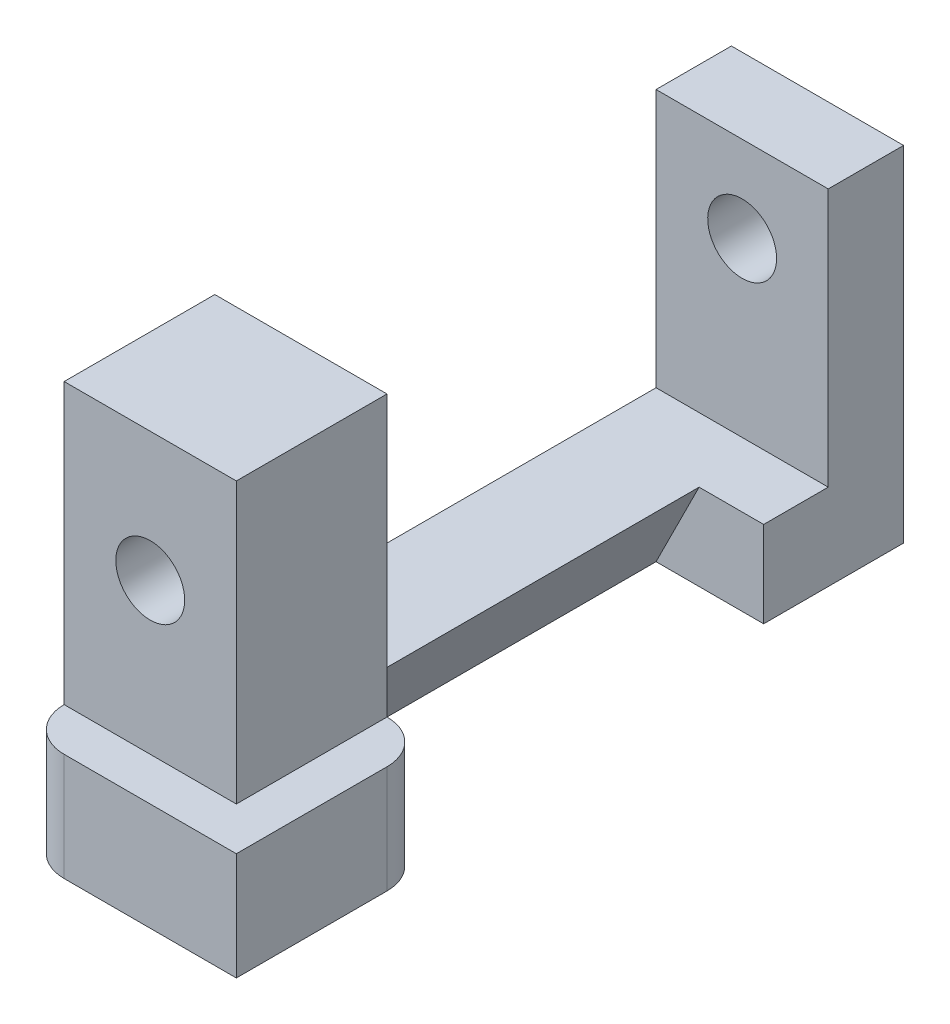
SolidWorks part; units mm, degrees
ref_plane "Front Plane" through (0, 0, 0) normal (0, 0, 1) x (1, 0, 0)
ref_plane "Top Plane" through (0, 0, 0) normal (0, 1, 0) x (1, 0, 0)
ref_plane "Right Plane" through (0, 0, 0) normal (1, 0, 0) x (0, 0, -1)
sketch "Sketch1" plane through (0, 0, 0) normal (1, 0, 0) x (0, 0, -1)
  line L0 (0, 0) -> (0, 16)
  line L1 (0, 16) -> (-3.5, 16)
  line L2 (-3.5, 16) -> (-3.5, 4)
  line L3 (-3.5, 4) -> (-24, 4)
  line L4 (-24, 4) -> (-24, 18)
  line L5 (-24, 18) -> (-31, 18)
  line L6 (-31, 18) -> (-31, 0)
  line L7 (-31, 0) -> (0, 0)
  dimension "D1" = 3.5
  dimension "D2" = 16
  dimension "D3" = 12
  dimension "D4" = 18
  dimension "D5" = 31
  dimension "D6" = 7
extrude "Boss-Extrude1" add sketch "Sketch1" against normal blind 8
sketch "Sketch3" plane through (-8, 0, 0) normal (-1, 0, 0) x (0, 0, 1)
  line L0 (3.5, 16) -> (3.5, 4) construction
  line L1 (3.5, 4) -> (24, 4)
  line L2 (3.5, 4) -> (3.5, 0)
  line L3 (3.5, 0) -> (24, 0)
  line L4 (24, 4) -> (24, 0)
  line L5 (24, 4) -> (24, 18) construction
  line L6 (31, 0) -> (0, 0) construction
  line L7 (3.5, 4) -> (24, 4) construction
extrude "Cut-Extrude1" [suppressed] cut sketch "Sketch3" against normal blind 4
sketch "Sketch5" plane through (0, 0, 3.5) normal (0, 0, 1) x (1, 0, 0)
  line L0 (-8, 0) -> (-3, 0)
  line L1 (-8, 0) -> (0, 0) construction
  line L2 (-3, 0) -> (-5, 4)
  line L3 (-5, 4) -> (-8, 4)
  line L4 (-8, 18) -> (-8, 0) construction
  line L5 (-8, 4) -> (-8, 0)
  dimension "D1" = 5
  dimension "D2" = 3
  dimension "D3" = 4
extrude "Cut-Extrude2" cut sketch "Sketch5" along normal up to surface (20.5 mm away) up to face at (-4, 11, 24)
mirror "Mirror1" about plane through (-8, 0, 0) normal (1, 0, 0) of "Cut-Extrude2", "Boss-Extrude1"
sketch "Sketch6" plane through (0, 0, 0) normal (1, 0, 0) x (0, 0, -1)
  line L1 (-33.8961, 19.8263) -> (1.3743, 19.8263)
  line L2 (-33.8961, 19.8263) -> (-33.8961, -2.4003)
  line L3 (-33.8961, -2.4003) -> (1.3743, -2.4003)
  line L4 (1.3743, 19.8263) -> (1.3743, -2.4003)
extrude "Cut-Extrude3" cut sketch "Sketch6" against normal blind 8
sketch "Sketch7" plane through (0, 0, 31) normal (0, 0, 1) x (1, 0, 0)
  line L0 (-16, 0) -> (-8, 0) construction
  line L1 (-8, 0) -> (-8, 18) construction
  circle A0 centre (-12, 12) radius 1.6
  point P4 (-12, 0)
  dimension "D1" = 3.2
  dimension "D2" = 12
  dimension "D3" = 4
sketch "Sketch9" plane through (0, 0, 3.5) normal (0, 0, 1) x (1, 0, 0)
  line L0 (-11, 4) -> (-13, 0)
  line L1 (-13, 0) -> (-8, 0)
  line L2 (-8, 0) -> (-8, 4)
  line L3 (-8, 0) -> (-8, 16) construction
  line L4 (-8, 4) -> (-11, 4)
extrude "Boss-Extrude2" add sketch "Sketch9" along normal blind 3
sketch "Sketch13" plane through (0, 0, 0) normal (0, -1, 0) x (1, 0, 0)
  line L0 (-14, 33) -> (-6, 33)
  line L1 (-6, 33) -> (-6, 26)
  line L2 (-16, 31) -> (-16, 0) construction
  line L3 (-16, 31) -> (-8, 31) construction
  line L4 (-8, 24) -> (-13, 24) construction
  line L5 (-8, 24) -> (-8, 31) construction
  line L6 (-16, 31) -> (-8, 31)
  line L7 (-8, 31) -> (-8, 24)
  arc A0 (-6, 26) -> (-8, 24) centre (-8, 26) cw
  arc A1 (-14, 33) -> (-16, 31) centre (-14, 31) ccw
  dimension "D1" = 2
  dimension "D2" = 2
extrude "Boss-Extrude7" add sketch "Sketch13" against normal blind 5
extrude "Cut-Extrude6" cut sketch "Sketch7" against normal through all
hole_wizard "Ø3.0mm Dowel Hole1" positions "Sketch14" profile "Sketch15" hole size "Ø3.0" standard "ANSI Metric"
sketch "Sketch14" plane through (0, 0, 0) normal (0, -1, 0) x (-1, 0, 0)
  line L0 (6, -33) -> (14, -33) construction
  line L1 (16, -31) -> (16, 0) construction
  point P0 (10.285, -29)
  dimension "D1" = 4
  dimension "D2" = 5.715
sketch "Sketch15" plane through (-10.285, 0, 29) normal (1, 0, 0) x (0, 0, -1)
  line L0 (0, 0) -> (0, 5.9013)
  line L1 (0, 5.9013) -> (1.5, 5)
  line L2 (1.5, 5) -> (1.5, 0)
  line L5 (1.5, 0) -> (0, 0)
  line L10 (0, 5.9013) -> (-1.5, 5) construction
  line L11 (0, -6.35) -> (0, 107.95) construction
  dimension "Hole Dia." = 3
  dimension "Hole Depth" = 5
  dimension "Drill Angle" = 118
